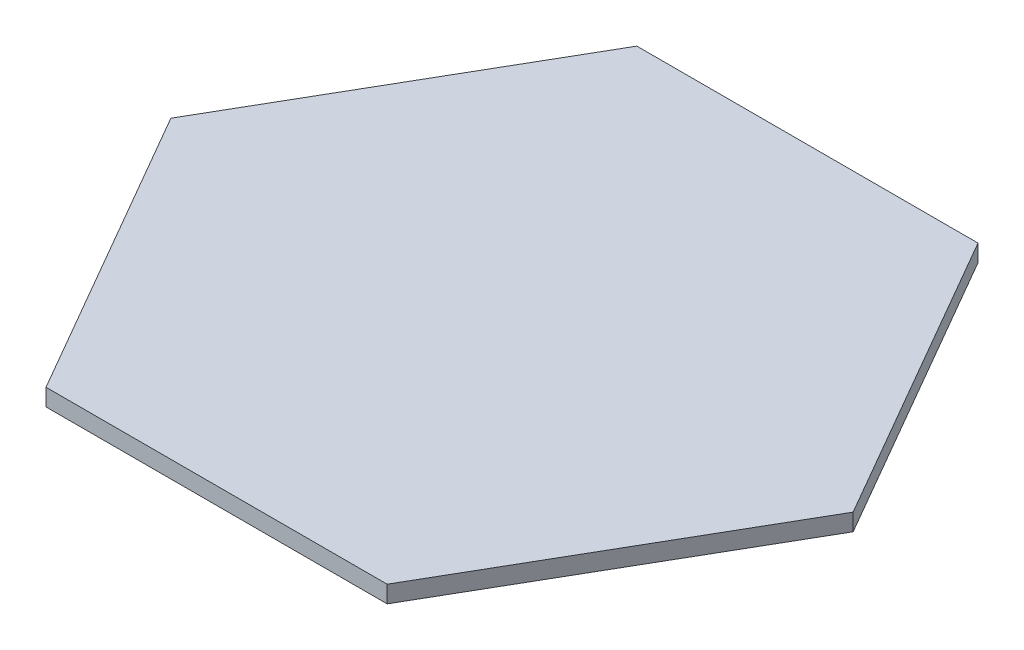
SolidWorks part; units mm, degrees
ref_plane "前基準面" through (0, 0, 0) normal (0, 0, 1) x (1, 0, 0)
ref_plane "上基準面" through (0, 0, 0) normal (0, 1, 0) x (1, 0, 0)
ref_plane "右基準面" through (0, 0, 0) normal (1, 0, 0) x (0, 0, -1)
sketch "草圖1" plane through (0, 0, 0) normal (0, 1, 0) x (1, 0, 0)
  line L1 (-20, 0) -> (-10, -17.3205)
  line L2 (-10, -17.3205) -> (10, -17.3205)
  line L3 (10, -17.3205) -> (20, 0)
  line L4 (20, 0) -> (10, 17.3205)
  line L5 (10, 17.3205) -> (-10, 17.3205)
  line L6 (-10, 17.3205) -> (-20, 0)
  circle A0 centre (0, 0) radius 17.3205 construction
  dimension "D1" = 20
extrude "填料-伸長1" add sketch "草圖1" along normal blind 1
